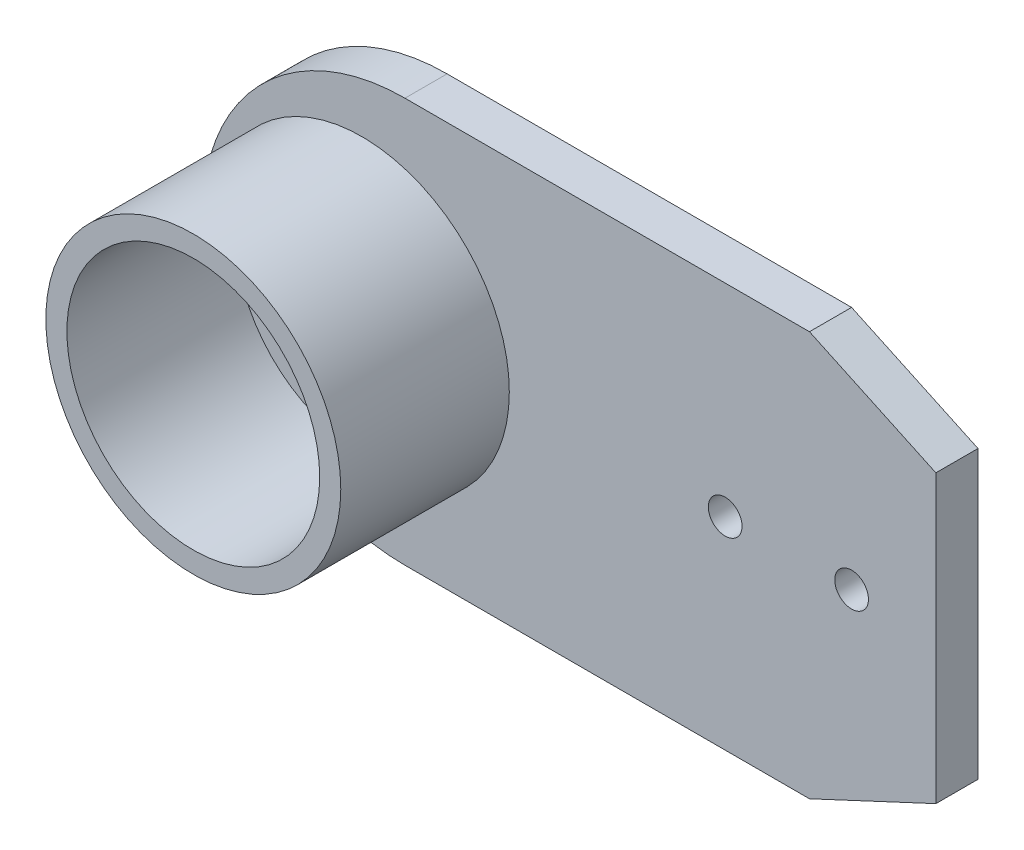
SolidWorks part; units mm, degrees
ref_plane "Front Plane" through (0, 0, 0) normal (0, 0, 1) x (1, 0, 0)
ref_plane "Top Plane" through (0, 0, 0) normal (0, 1, 0) x (1, 0, 0)
ref_plane "Right Plane" through (0, 0, 0) normal (1, 0, 0) x (0, 0, -1)
sketch "Sketch1" plane through (0, 0, 0) normal (0, 0, 1) x (1, 0, 0)
  line L1 (-19.5, 24) -> (43.5, 24)
  line L3 (-19.5, -24) -> (43.5, -24)
  line L4 (43.5, 24) -> (43.5, -24)
  arc A0 (-19.5, 24) -> (-19.5, -24) centre (-19.5, 0) ccw
  point P0 (0, 0)
  dimension "D1" = 48
extrude "Boss-Extrude2" add sketch "Sketch1" along normal blind 5
sketch "Sketch2" plane through (0, 0, 5) normal (0, 0, 1) x (1, 0, 0)
  line L0 (43.5, -24) -> (43.5, 24) construction
  circle A0 centre (33.5, 0) radius 2
  circle A1 centre (18.5, 0) radius 2
  dimension "D1" = 4
  dimension "D2" = 4
  dimension "D3" = 10
  dimension "D4" = 25
extrude "Cut-Extrude1" cut sketch "Sketch2" against normal through all
sketch "Sketch3" plane through (0, 0, 5) normal (0, 0, 1) x (1, 0, 0)
  circle A0 centre (-24.6173, 0) radius 5
  dimension "D1" = 10
extrude "Cut-Extrude2" cut sketch "Sketch3" against normal blind 5
sketch "Sketch9" plane through (0, 0, 5) normal (0, 0, 1) x (1, 0, 0)
  line L0 (28.5, 24) -> (43.5, 17)
  line L1 (43.5, 24) -> (-19.5, 24) construction
  line L2 (43.5, -24) -> (43.5, 24) construction
  line L3 (43.5, -17) -> (28.5, -24)
  line L4 (-19.5, -24) -> (43.5, -24) construction
  line L5 (28.5, 24) -> (43.5, 24)
  line L6 (43.5, 24) -> (43.5, 17)
  line L7 (28.5, -24) -> (43.5, -24)
  line L8 (43.5, -24) -> (43.5, -17)
  dimension "D1" = 7
  dimension "D2" = 15
  dimension "D3" = 7
  dimension "D4" = 15
extrude "Cut-Extrude5" cut sketch "Sketch9" against normal through all
sketch "Sketch10" plane through (0, 0, 5) normal (0, 0, 1) x (1, 0, 0)
  circle A0 centre (-24.6173, 0) radius 17.5
  dimension "D1" = 35
extrude "Boss-Extrude5" add sketch "Sketch10" along normal blind 20
sketch "Sketch11" plane through (0, 0, 25) normal (0, 0, 1) x (1, 0, 0)
  circle A0 centre (-24.6173, 0) radius 15
  dimension "D1" = 30
extrude "Cut-Extrude6" cut sketch "Sketch11" against normal blind 20
